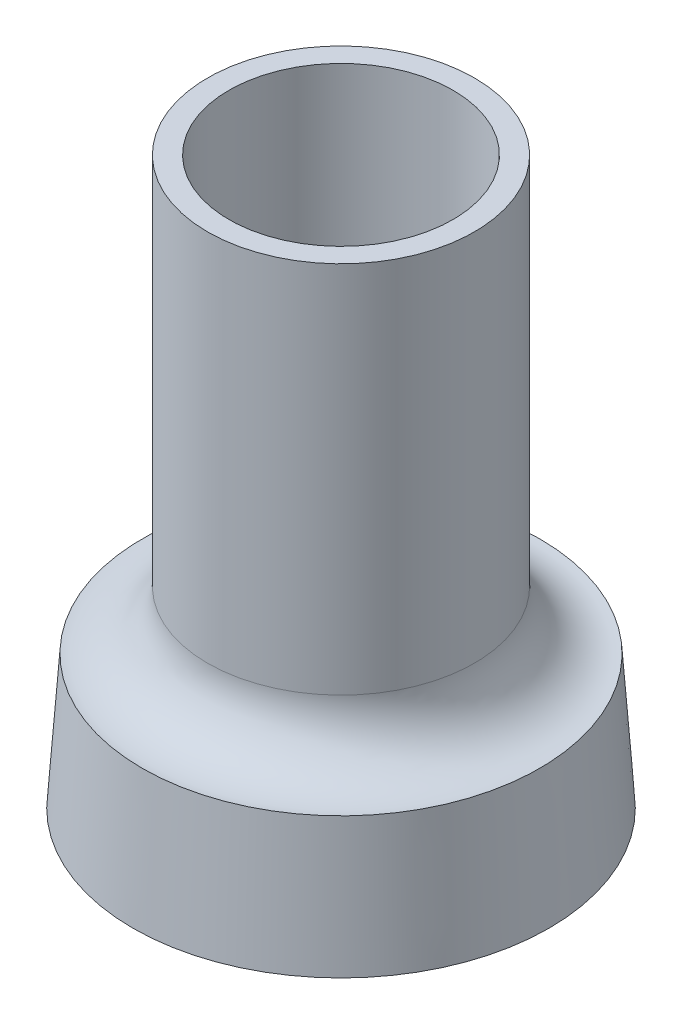
SolidWorks part; units mm, degrees
ref_plane "Płaszczyzna przednia" through (0, 0, 0) normal (0, 0, 1) x (1, 0, 0)
ref_plane "Płaszczyzna górna" through (0, 0, 0) normal (0, 1, 0) x (1, 0, 0)
ref_plane "Płaszczyzna prawa" through (0, 0, 0) normal (1, 0, 0) x (0, 0, -1)
sketch "Szkic2" plane through (0, 0, 0) normal (1, 0, 0) x (0, 0, -1)
  line L0 (0, 0) -> (0, 5.3) construction
  line L1 (0, 0) -> (1.95, 0) construction
  line L2 (1.95, 0) -> (1.7747, 2.5071) construction
  line L3 (0, 5.3) -> (1.25, 5.3) construction
  line L4 (1.25, 5.3) -> (1.25, 1.8)
  line L5 (1.8623, 1.2535) -> (1.95, 0)
  arc A0 (1.25, 1.8) -> (1.8623, 1.2535) centre (1.8, 1.8) ccw
  point P9 (0, 0)
  dimension "D6" = 0.55
  dimension "D1" = 5.3
  dimension "D2" = 1.95
  dimension "D3" = 4
  dimension "D4" = 1.25
  dimension "D5" = 3.5
revolve "Obrót-cienka ścianka3" add sketch "Szkic2" angle 360 about L0
